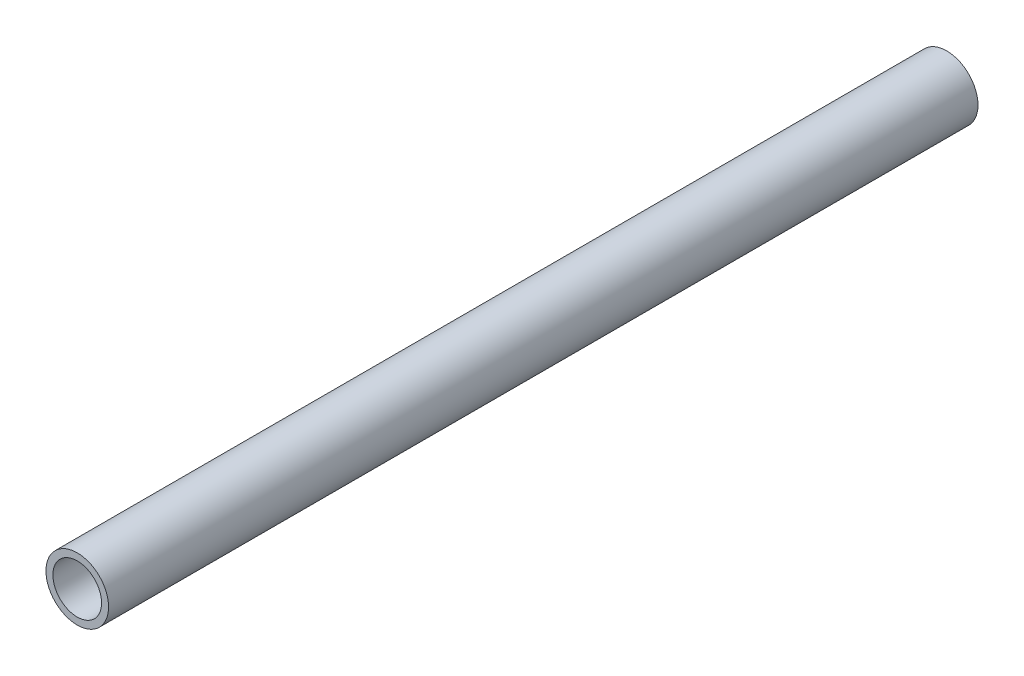
SolidWorks part; units mm, degrees
ref_plane "Front Plane" through (0, 0, 0) normal (0, 0, 1) x (1, 0, 0)
ref_plane "Top Plane" through (0, 0, 0) normal (0, 1, 0) x (1, 0, 0)
ref_plane "Right Plane" through (0, 0, 0) normal (1, 0, 0) x (0, 0, -1)
sketch "Sketch1" plane through (0, 0, 0) normal (0, 0, 1) x (1, 0, 0)
  line L0 (-4.5, 0) -> (4.5, 0) construction
  line L1 (-3.5, 0) -> (3.5, 0) construction
  circle A0 centre (0, 0) radius 4.5 construction
  circle A1 centre (0, 0) radius 3.5 construction
  point P4 (0, 0)
  point P10 (0, 0)
  dimension "ID" = 7
  dimension "OD" = 9
  dimension "Wall Thickness" = 1
sketch "Sketch2" plane through (0, 0, 0) normal (1, 0, 0) x (0, 0, -1)
  line L0 (150, 0) -> (-150, 0) construction
  line L2 (-150, -4.5) -> (150, -4.5) construction
  line L3 (-150, -4.5) -> (-150, 4.5) construction
  line L4 (-150, 4.5) -> (150, 4.5) construction
  line L5 (150, -4.5) -> (150, 4.5) construction
  line L6 (0, 4.5) -> (0, -4.5) construction
  line L7 (-150, 0) -> (150, 0) construction
  point P0 (-134.25, 0)
  point P3 (0, 0)
  point P4 (0, 0)
  point P6 (134.25, 0)
  dimension "D2" = 15.75
  dimension "D3" = 15.75
  dimension "Length" = 300
sketch "Sketch3" plane through (0, 0, 0) normal (0, 0, 1) x (1, 0, 0)
  circle A0 centre (0, 0) radius 4.5
  circle A1 centre (0, 0) radius 3.5 construction
  circle A2 centre (0, 0) radius 3.5
  dimension "D1" = 9
extrude "Boss-Extrude1" add sketch "Sketch3" along normal mid plane 300
sketch "Sketch4" plane through (0, 0, 150) normal (0, 0, 1) x (1, 0, 0)
  circle A0 centre (0, 0) radius 4.5
  circle A1 centre (0, 0) radius 4.5 construction
extrude "Cut-Extrude1" cut sketch "Sketch4" against normal blind 175
equation "\"D2@Sketch2\" = \"OD@Sketch1\" * 1.75"
equation "\"D3@Sketch2\"=\"D2@Sketch2\""
equation "\"D1@Sketch3\" = \"OD@Sketch1\""
equation "\"D1@Boss-Extrude1\"=\"Length@Sketch2\""
